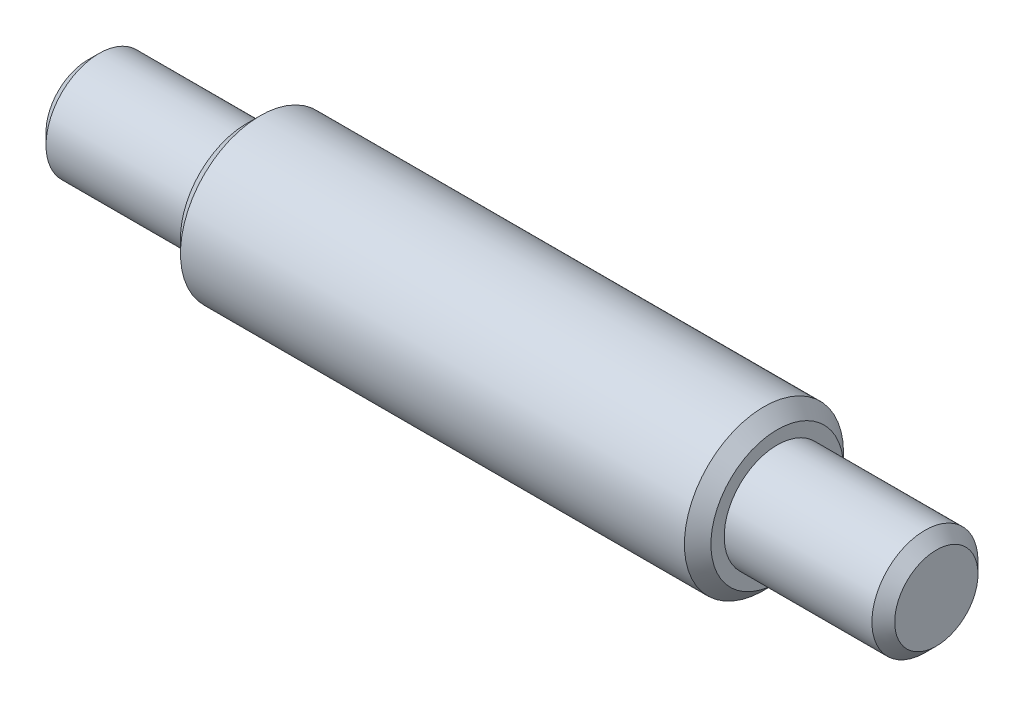
SolidWorks part; units mm, degrees
ref_plane "Front Plane" through (0, 0, 0) normal (0, 0, 1) x (1, 0, 0)
ref_plane "Top Plane" through (0, 0, 0) normal (0, 1, 0) x (1, 0, 0)
ref_plane "Right Plane" through (0, 0, 0) normal (1, 0, 0) x (0, 0, -1)
sketch "Sketch1" plane through (0, 0, 0) normal (0, 0, 1) x (1, 0, 0)
  line L0 (-6, 1.5705) -> (-6, 0)
  line L1 (-6, 0) -> (26, 0)
  line L2 (26, 0) -> (26, 1.5705)
  line L3 (26, 1.5705) -> (25.5705, 2)
  line L4 (25.5705, 2) -> (20, 2)
  line L5 (20, 2) -> (20, 2.5)
  line L6 (20, 2.5) -> (19.5, 3)
  line L7 (19.5, 3) -> (0.5, 3)
  line L8 (0.5, 3) -> (0, 2.5)
  line L9 (0, 2.5) -> (0, 2)
  line L10 (0, 2) -> (-5.5705, 2)
  line L11 (-5.5705, 2) -> (-6, 1.5705)
  line L12 (-6, 0) -> (26, 0) construction
revolve "Revolve1" add sketch "Sketch1" angle 360 about L12
